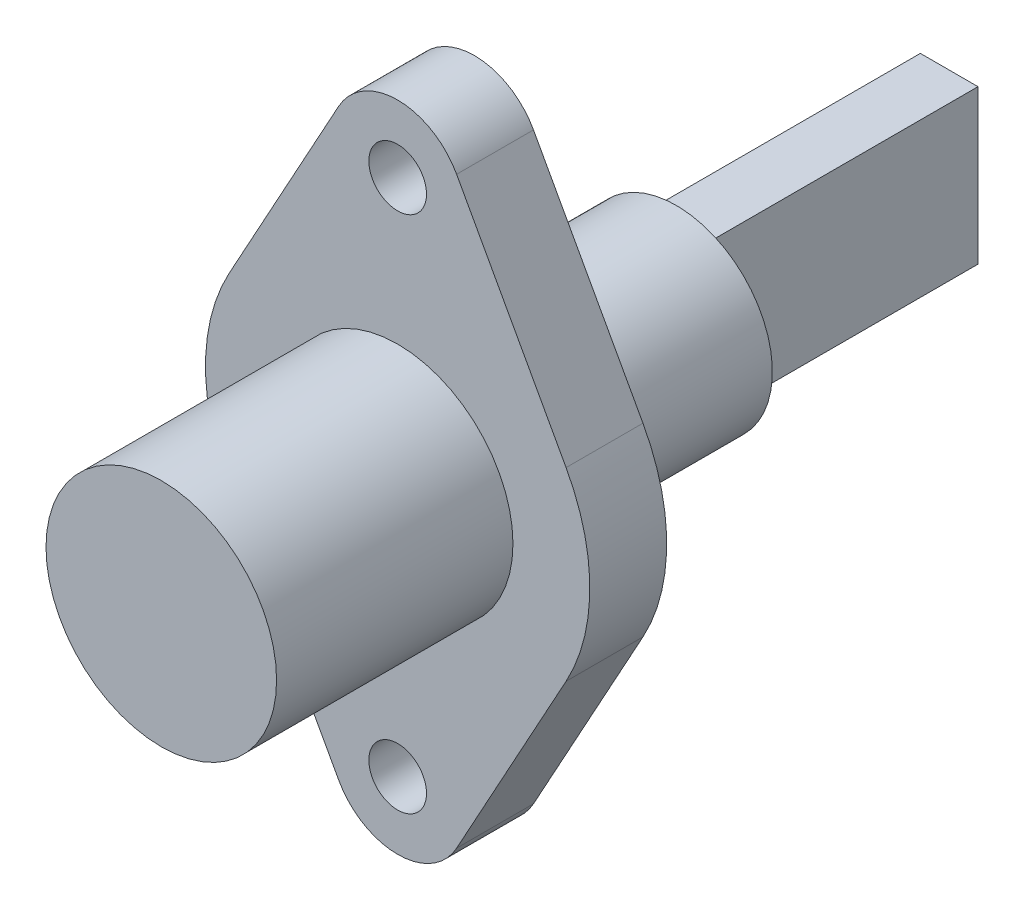
SolidWorks part; units mm, degrees
material "Custom Plastic"
ref_plane "X-Y Datum" through (0, 0, 0) normal (0, 0, 1) x (1, 0, 0)
ref_plane "X-Z Datum" through (0, 0, 0) normal (0, 1, 0) x (1, 0, 0)
ref_plane "Y-Z Datum" through (0, 0, 0) normal (1, 0, 0) x (0, 0, -1)
sketch "Sketch1" plane through (0, 0, 0) normal (0, 0, 1) x (1, 0, 0)
  line L0 (0, 17) -> (0, -17) construction
  line L1 (-10, 0) -> (10, 0) construction
  line L2 (-3.0676, 15.1852) -> (-8.7646, 4.8148)
  line L3 (3.0676, 15.1852) -> (8.7646, 4.8148)
  line L4 (3.0676, -15.1852) -> (8.7646, -4.8148)
  line L5 (-3.0676, -15.1852) -> (-8.7646, -4.8148)
  circle A0 centre (0, 0) radius 10
  circle A3 centre (0, 13.5) radius 3.5
  circle A4 centre (0, -13.5) radius 3.5
  circle A5 centre (0, 13.5) radius 1.5
  circle A6 centre (0, -13.5) radius 1.5
  point P4 (0, 0)
  point P8 (0, 0)
  dimension "D3" = 3
  dimension "D1" = 34
  dimension "D2" = 20
extrude "Boss-Extrude1" add sketch "Sketch1" along normal blind 4 contours A4 A6 | A0 A4 L4 | A0 | A3 A0 L3 | A3 A5 | A3 L2 A0 | L5 A4 A0
sketch "Sketch2" plane through (0, 0, 4) normal (0, 0, 1) x (1, 0, 0)
  circle A0 centre (0, 0) radius 6
  dimension "D1" = 12
extrude "Boss-Extrude2" add sketch "Sketch2" along normal blind 12.3
sketch "Sketch3" plane through (0, 0, 0) normal (0, 0, -1) x (-1, 0, 0)
  circle A0 centre (0, 0) radius 7.5
  dimension "D1" = 15
extrude "Boss-Extrude3" add sketch "Sketch3" along normal blind 0.5
sketch "Sketch4" plane through (0, 0, -0.5) normal (0, 0, -1) x (-1, 0, 0)
  line L1 (-1.5, 4) -> (1.5, 4)
  line L2 (-1.5, 4) -> (-1.5, -4)
  line L3 (-1.5, -4) -> (1.5, -4)
  line L4 (1.5, 4) -> (1.5, -4)
  line L5 (-1.5, 4) -> (1.5, -4) construction
  line L6 (-1.5, -4) -> (1.5, 4) construction
  point P0 (0, 0)
  point P6 (1.9066, -4.1984)
  dimension "D1" = 8
  dimension "D2" = 3
extrude "Boss-Extrude4" add sketch "Sketch4" along normal blind 24.2
sketch "Sketch5" plane through (0, 0, -0.5) normal (0, 0, -1) x (-1, 0, 0)
  circle A0 centre (0, 0) radius 5
  dimension "D1" = 10
extrude "Boss-Extrude5" add sketch "Sketch5" along normal blind 10
